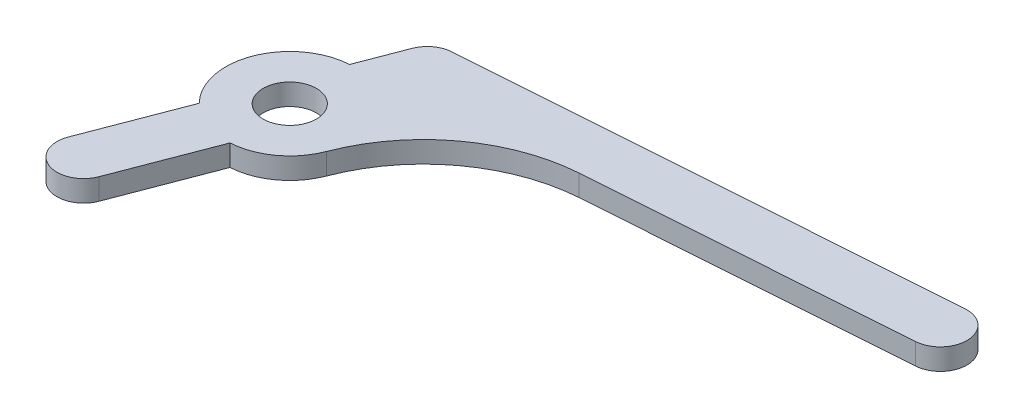
SolidWorks part; units mm, degrees
ref_plane "Front Plane" through (0, 0, 0) normal (0, 0, 1) x (1, 0, 0)
ref_plane "Top Plane" through (0, 0, 0) normal (0, 1, 0) x (1, 0, 0)
ref_plane "Right Plane" through (0, 0, 0) normal (1, 0, 0) x (0, 0, -1)
sketch "Sketch1" plane through (0, 0, 0) normal (0, 1, 0) x (1, 0, 0)
  line L0 (0, 0) -> (-6.8061, -17.7927) construction
  line L1 (2.9654, -1.1343) -> (-3.8406, -18.927)
  line L2 (-2.9654, 1.1343) -> (-9.7715, -16.6583)
  line L3 (0, 0) -> (4.5374, 11.8618) construction
  line L4 (-2.9654, 1.1343) -> (1.5719, 12.9961)
  line L5 (2.9654, -1.1343) -> (7.5028, 10.7274)
  line L6 (4.5374, 11.8618) -> (61.6874, 15.9254) construction
  line L7 (4.3122, 15.0288) -> (61.4622, 19.0924)
  line L8 (4.7626, 8.6948) -> (61.9126, 12.7584)
  line L9 (7.1328, -2.7285) -> (0, 0) construction
  circle A0 centre (0, 0) radius 2.7781 construction
  arc A1 (2.9654, -1.1343) -> (-2.9654, 1.1343) centre (0, 0) ccw
  arc A2 (-9.7715, -16.6583) -> (-3.8406, -18.927) centre (-6.8061, -17.7927) ccw
  arc A3 (-2.9654, 1.1343) -> (2.9654, -1.1343) centre (0, 0) ccw
  arc A4 (7.5028, 10.7274) -> (1.5719, 12.9961) centre (4.5374, 11.8618) ccw
  arc A5 (4.3122, 15.0288) -> (4.7626, 8.6948) centre (4.5374, 11.8618) ccw
  arc A6 (61.9126, 12.7584) -> (61.4622, 19.0924) centre (61.6874, 15.9254) ccw
  circle A7 centre (0, 0) radius 7.6369
  arc A8 (7.1328, -2.7285) -> (24.4167, 10.0923) centre (25.837, -9.8832) cw
  point P4 (-3.403, -8.8963)
  point P11 (2.2687, 5.9309)
  point P16 (33.1124, 13.8936)
  dimension "D1" = 5.5562
  dimension "D2" = 3.175
  dimension "D3" = 12.7
  dimension "D4" = 19.05
  dimension "D5" = 115
  dimension "D6" = 57.15
extrude "Boss-Extrude1" add sketch "Sketch1" along normal blind 2.54 contours L4 A7 L2 | L5 A7 L4 A1 | L2 A7 L1 A3 | L1 A7 L5 | A7 L5 L8 A5 L4 | L8 A6 L7 A4 L5 | A7 A8 L8 L5 | A4 A5 L8 L5 | A7 L2 A2 L1
